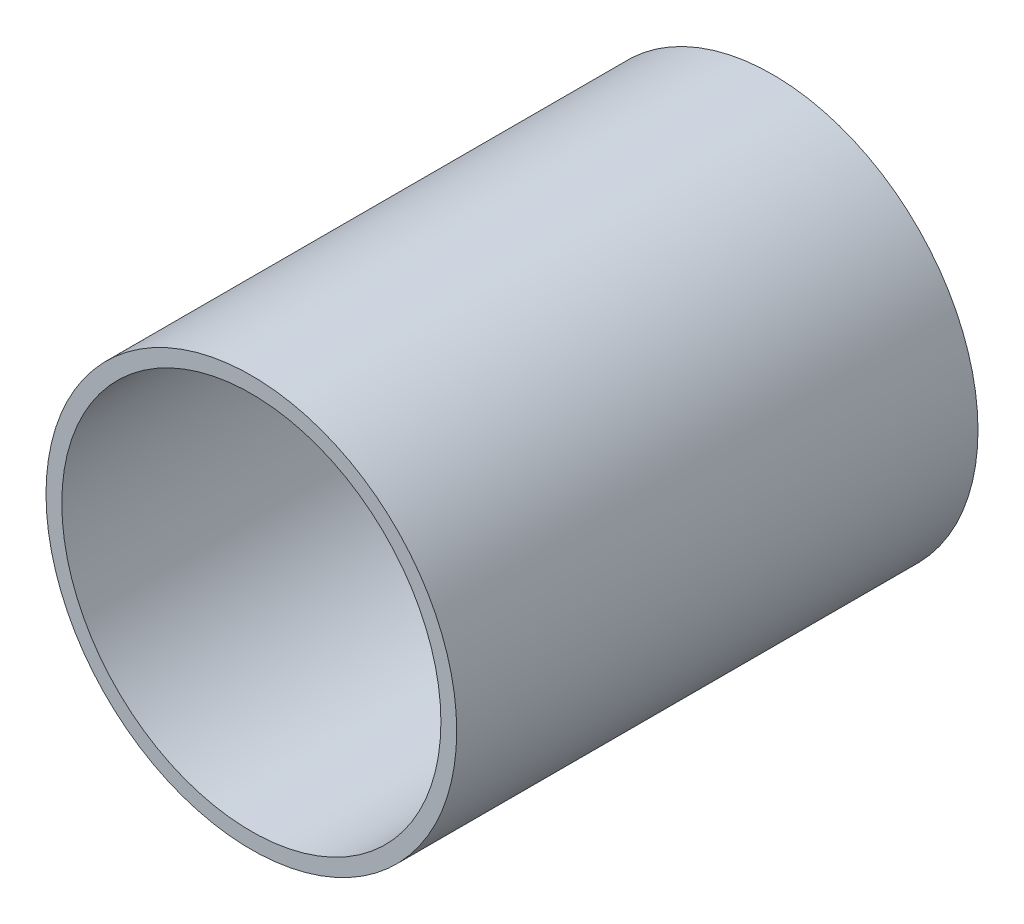
SolidWorks part; units mm, degrees
material "Acrylic (Medium-high impact)"
ref_plane "Front Plane" through (0, 0, 0) normal (0, 0, 1) x (1, 0, 0)
ref_plane "Top Plane" through (0, 0, 0) normal (0, 1, 0) x (1, 0, 0)
ref_plane "Right Plane" through (0, 0, 0) normal (1, 0, 0) x (0, 0, -1)
sketch "Sketch2" plane through (0, 0, 104.775) normal (0, 0, -1) x (-1, 0, 0)
  circle A0 centre (0, 0) radius 82.55
  circle A1 centre (0, 0) radius 76.2
  dimension "D1" = 152.4
  dimension "D2" = 6.35
extrude "Boss-Extrude1" add sketch "Sketch2" along normal up to surface (209.55 mm away)
